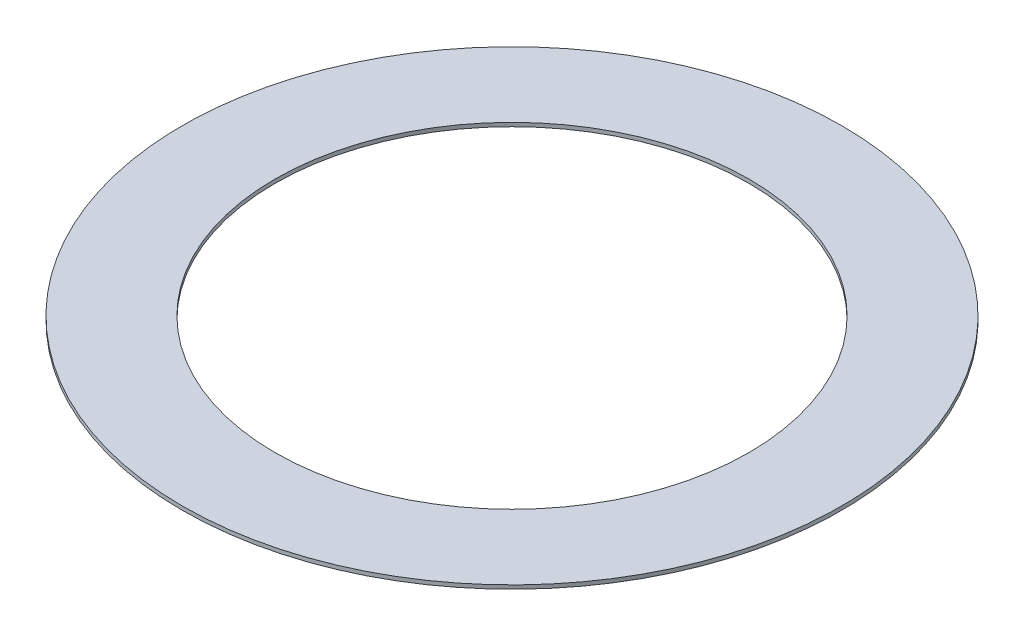
SolidWorks part; units mm, degrees
ref_plane "Front Plane" through (0, 0, 0) normal (0, 0, 1) x (1, 0, 0)
ref_plane "Top Plane" through (0, 0, 0) normal (0, 1, 0) x (1, 0, 0)
ref_plane "Right Plane" through (0, 0, 0) normal (1, 0, 0) x (0, 0, -1)
sketch "Sketch1" plane through (0, 0, 0) normal (0, 1, 0) x (1, 0, 0)
  circle A0 centre (0, 0) radius 11.0744
  circle A1 centre (0, 0) radius 7.9629
  dimension "D1" = 15.9258
  dimension "D2" = 22.1488
extrude "Boss-Extrude1" add sketch "Sketch1" along normal blind 0.127
